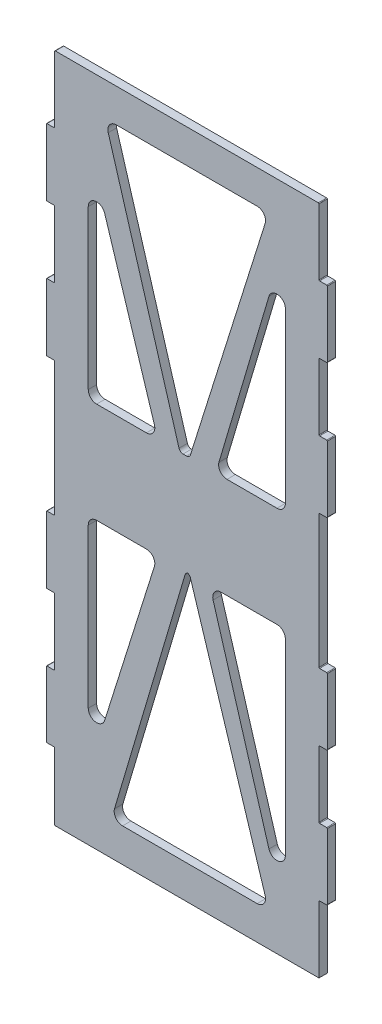
SolidWorks part; units mm, degrees
ref_plane "Front Plane" through (0, 0, 0) normal (0, 0, 1) x (1, 0, 0)
ref_plane "Top Plane" through (0, 0, 0) normal (0, 1, 0) x (1, 0, 0)
ref_plane "Right Plane" through (0, 0, 0) normal (1, 0, 0) x (0, 0, -1)
sketch "Model" plane through (0, 0, 0) normal (0, 0, 1) x (1, 0, 0)
  line L0 (431.4229, 190.2889) -> (331.6644, 190.2889)
  line L1 (331.4104, 190.5429) -> (331.4104, 215.6889)
  line L2 (382.7866, 297.1274) -> (411.0759, 207.1158)
  line L3 (394.4055, 298.2389) -> (415.5479, 298.2389)
  line L4 (418.7229, 295.0639) -> (418.7229, 224.0253)
  line L5 (354.718, 431.5889) -> (408.047, 431.5889)
  line L6 (411.0759, 427.4619) -> (382.7866, 337.4504)
  line L7 (418.7229, 403.3565) -> (418.7229, 339.5139)
  line L8 (350.3144, 400.448) -> (369.1659, 340.4658)
  line L9 (366.137, 336.3389) -> (347.2854, 336.3389)
  line L10 (344.1104, 339.5139) -> (344.1104, 399.496)
  line L11 (393.5791, 340.4162) -> (412.5039, 404.2589)
  line L12 (415.5479, 336.3389) -> (396.6232, 336.3389)
  line L13 (369.1659, 294.1119) -> (350.3144, 234.1298)
  line L14 (347.2854, 298.2389) -> (366.137, 298.2389)
  line L15 (344.1104, 235.0818) -> (344.1104, 295.0639)
  line L16 (354.0503, 207.0662) -> (380.7397, 297.1026)
  line L17 (408.047, 202.9889) -> (357.0944, 202.9889)
  line L18 (412.5049, 223.1197) -> (391.3624, 294.1582)
  line L19 (381.2721, 336.3389) -> (379.9925, 336.3389)
  line L20 (378.471, 337.4736) -> (351.6749, 427.5082)
  line L21 (431.4229, 215.4349) -> (431.4229, 190.2889)
  line L22 (434.3439, 215.6889) -> (431.6769, 215.6889)
  line L23 (331.4104, 241.3429) -> (331.4104, 266.2349)
  line L24 (328.4894, 241.0889) -> (331.1564, 241.0889)
  line L25 (331.1564, 266.4889) -> (328.4894, 266.4889)
  line L26 (328.2354, 266.7429) -> (328.2354, 291.6349)
  line L27 (328.4894, 291.8889) -> (331.1564, 291.8889)
  line L28 (331.4104, 292.1429) -> (331.4104, 342.4349)
  line L29 (331.4104, 368.3429) -> (331.4104, 393.2349)
  line L30 (331.1564, 342.6889) -> (328.4894, 342.6889)
  line L31 (328.2354, 342.9429) -> (328.2354, 367.8349)
  line L32 (328.4894, 368.0889) -> (331.1564, 368.0889)
  line L33 (331.1564, 393.4889) -> (328.4894, 393.4889)
  line L34 (328.2354, 393.7429) -> (328.2354, 418.6349)
  line L35 (328.4894, 418.8889) -> (331.1564, 418.8889)
  line L36 (331.4104, 419.1429) -> (331.4104, 444.0349)
  line L37 (331.6644, 444.2889) -> (431.1689, 444.2889)
  line L38 (431.4229, 444.0349) -> (431.4229, 419.1429)
  line L39 (431.4229, 393.2349) -> (431.4229, 368.3429)
  line L40 (431.4229, 342.4349) -> (431.4229, 292.1429)
  line L41 (431.6769, 418.8889) -> (434.3439, 418.8889)
  line L42 (434.5979, 418.6349) -> (434.5979, 393.7429)
  line L43 (434.3439, 393.4889) -> (431.6769, 393.4889)
  line L44 (434.3439, 342.6889) -> (431.6769, 342.6889)
  line L45 (431.6769, 368.0889) -> (434.3439, 368.0889)
  line L46 (434.5979, 367.8349) -> (434.5979, 342.9429)
  line L47 (434.5979, 291.6349) -> (434.5979, 266.7429)
  line L48 (431.6769, 291.8889) -> (434.3439, 291.8889)
  line L49 (431.6769, 241.0889) -> (434.3439, 241.0889)
  line L50 (431.4229, 266.2349) -> (431.4229, 241.3429)
  line L51 (434.3439, 266.4889) -> (431.6769, 266.4889)
  line L52 (434.5979, 240.8349) -> (434.5979, 215.9429)
  line L53 (328.2354, 216.1969) -> (328.2354, 240.8349)
  line L54 (328.4894, 215.9429) -> (331.1564, 215.9429)
  arc A0 (331.4104, 190.5429) -> (331.6644, 190.2889) centre (331.6644, 190.5429) ccw
  arc A1 (382.7866, 297.1274) -> (381.7669, 298.1598) centre (381.2721, 296.6514) ccw
  arc A2 (381.7669, 298.1598) -> (380.7397, 297.1026) centre (382.2617, 296.6514) ccw
  arc A3 (394.4055, 298.2389) -> (391.3624, 294.1582) centre (394.4055, 295.0639) ccw
  arc A4 (418.7229, 295.0639) -> (415.5479, 298.2389) centre (415.5479, 295.0639) ccw
  arc A5 (354.718, 431.5889) -> (351.6749, 427.5082) centre (354.718, 428.4139) ccw
  arc A6 (411.0759, 427.4619) -> (408.047, 431.5889) centre (408.047, 428.4139) ccw
  arc A7 (418.7229, 403.3565) -> (412.5039, 404.2589) centre (415.5479, 403.3565) ccw
  arc A8 (350.3144, 400.448) -> (344.1104, 399.496) centre (347.2854, 399.496) ccw
  arc A9 (366.137, 336.3389) -> (369.1659, 340.4658) centre (366.137, 339.5139) ccw
  arc A10 (344.1104, 339.5139) -> (347.2854, 336.3389) centre (347.2854, 339.5139) ccw
  arc A11 (393.5791, 340.4162) -> (396.6232, 336.3389) centre (396.6232, 339.5139) ccw
  arc A12 (415.5479, 336.3389) -> (418.7229, 339.5139) centre (415.5479, 339.5139) ccw
  arc A13 (369.1659, 294.1119) -> (366.137, 298.2389) centre (366.137, 295.0639) ccw
  arc A14 (347.2854, 298.2389) -> (344.1104, 295.0639) centre (347.2854, 295.0639) ccw
  arc A15 (344.1104, 235.0818) -> (350.3144, 234.1298) centre (347.2854, 235.0818) ccw
  arc A16 (354.0503, 207.0662) -> (357.0944, 202.9889) centre (357.0944, 206.1639) ccw
  arc A17 (408.047, 202.9889) -> (411.0759, 207.1158) centre (408.047, 206.1639) ccw
  arc A18 (412.5049, 223.1197) -> (418.7229, 224.0253) centre (415.5479, 224.0253) ccw
  arc A19 (381.2721, 336.3389) -> (382.7866, 337.4504) centre (381.2721, 337.9264) ccw
  arc A20 (378.471, 337.4736) -> (379.9925, 336.3389) centre (379.9925, 337.9264) ccw
  arc A21 (431.6769, 215.6889) -> (431.4229, 215.4349) centre (431.6769, 215.4349) ccw
  arc A22 (434.3439, 215.6889) -> (434.5979, 215.9429) centre (434.3439, 215.9429) ccw
  arc A23 (331.1564, 241.0889) -> (331.4104, 241.3429) centre (331.1564, 241.3429) ccw
  arc A24 (328.4894, 241.0889) -> (328.2354, 240.8349) centre (328.4894, 240.8349) ccw
  arc A25 (331.4104, 266.2349) -> (331.1564, 266.4889) centre (331.1564, 266.2349) ccw
  arc A26 (328.2354, 266.7429) -> (328.4894, 266.4889) centre (328.4894, 266.7429) ccw
  arc A27 (328.4894, 291.8889) -> (328.2354, 291.6349) centre (328.4894, 291.6349) ccw
  arc A28 (331.1564, 291.8889) -> (331.4104, 292.1429) centre (331.1564, 292.1429) ccw
  arc A29 (331.1564, 368.0889) -> (331.4104, 368.3429) centre (331.1564, 368.3429) ccw
  arc A30 (331.4104, 342.4349) -> (331.1564, 342.6889) centre (331.1564, 342.4349) ccw
  arc A31 (328.2354, 342.9429) -> (328.4894, 342.6889) centre (328.4894, 342.9429) ccw
  arc A32 (328.4894, 368.0889) -> (328.2354, 367.8349) centre (328.4894, 367.8349) ccw
  arc A33 (331.4104, 393.2349) -> (331.1564, 393.4889) centre (331.1564, 393.2349) ccw
  arc A34 (328.2354, 393.7429) -> (328.4894, 393.4889) centre (328.4894, 393.7429) ccw
  arc A35 (328.4894, 418.8889) -> (328.2354, 418.6349) centre (328.4894, 418.6349) ccw
  arc A36 (331.1564, 418.8889) -> (331.4104, 419.1429) centre (331.1564, 419.1429) ccw
  arc A37 (331.6644, 444.2889) -> (331.4104, 444.0349) centre (331.6644, 444.0349) ccw
  arc A38 (431.4229, 444.0349) -> (431.1689, 444.2889) centre (431.1689, 444.0349) ccw
  arc A39 (431.6769, 393.4889) -> (431.4229, 393.2349) centre (431.6769, 393.2349) ccw
  arc A40 (431.6769, 342.6889) -> (431.4229, 342.4349) centre (431.6769, 342.4349) ccw
  arc A41 (431.4229, 419.1429) -> (431.6769, 418.8889) centre (431.6769, 419.1429) ccw
  arc A42 (434.5979, 418.6349) -> (434.3439, 418.8889) centre (434.3439, 418.6349) ccw
  arc A43 (434.3439, 393.4889) -> (434.5979, 393.7429) centre (434.3439, 393.7429) ccw
  arc A44 (434.3439, 342.6889) -> (434.5979, 342.9429) centre (434.3439, 342.9429) ccw
  arc A45 (431.4229, 368.3429) -> (431.6769, 368.0889) centre (431.6769, 368.3429) ccw
  arc A46 (434.5979, 367.8349) -> (434.3439, 368.0889) centre (434.3439, 367.8349) ccw
  arc A47 (434.5979, 291.6349) -> (434.3439, 291.8889) centre (434.3439, 291.6349) ccw
  arc A48 (431.4229, 292.1429) -> (431.6769, 291.8889) centre (431.6769, 292.1429) ccw
  arc A49 (431.4229, 241.3429) -> (431.6769, 241.0889) centre (431.6769, 241.3429) ccw
  arc A50 (431.6769, 266.4889) -> (431.4229, 266.2349) centre (431.6769, 266.2349) ccw
  arc A51 (434.3439, 266.4889) -> (434.5979, 266.7429) centre (434.3439, 266.7429) ccw
  arc A52 (434.5979, 240.8349) -> (434.3439, 241.0889) centre (434.3439, 240.8349) ccw
  arc A53 (328.2354, 216.1969) -> (328.4894, 215.9429) centre (328.4894, 216.1969) ccw
  arc A54 (331.4104, 215.6889) -> (331.1564, 215.9429) centre (331.1564, 215.6889) ccw
extrude "Boss-Extrude3" add sketch "Model" along normal blind 3.175 contours L5 A6 L6 A19 L19 A20 L20 A5 | L3 A4 L4 A18 L18 A3 | L2 A17 L17 A16 L16 A2 A1 | L8 A9 L9 A10 L10 A8 | L7 A12 L12 A11 L11 A7 | L13 A15 L15 A14 L14 A13 | L0 A0 L1 A54 L54 A53 L53 A24 L24 A23 L23 A25 L25 A26 L26 A27 L27 A28 L28 A30 L30 A31 L31 A32 L32 A29 L29 A33 L33 A34 L34 A35 L35 A36 L36 A37 L37 A38 L38 A41 L41 A42 L42 A43 L43 A39 L39 A45 L45 A46 L46 A44 L44 A40 L40 A48 L48 A47 L47 A51 L51 A50 L50 A49 L49 A52 L52 A22 L22 A21 L21
